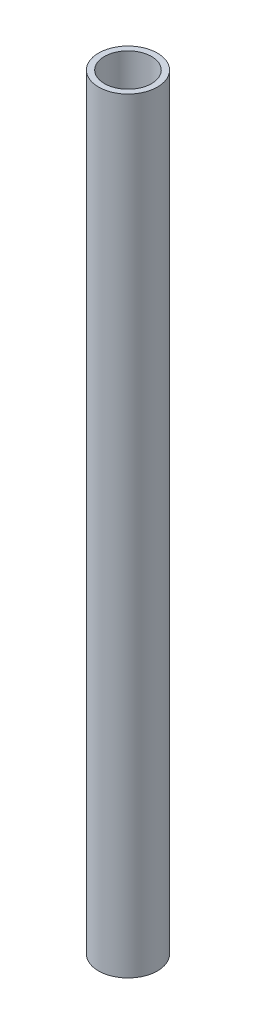
SolidWorks part; units mm, degrees
material "Hexcel AS4C (3000 丝)"
ref_plane "前视基准面" through (0, 0, 0) normal (0, 0, 1) x (1, 0, 0)
ref_plane "上视基准面" through (0, 0, 0) normal (0, 1, 0) x (1, 0, 0)
ref_plane "右视基准面" through (0, 0, 0) normal (1, 0, 0) x (0, 0, -1)
sketch "草图1" plane through (0, 0, 0) normal (0, 1, 0) x (1, 0, 0)
  circle A0 centre (0, 0) radius 10
  circle A1 centre (0, 0) radius 8
  dimension "D1" = 20
  dimension "D2" = 16
extrude "凸台-拉伸1" add sketch "草图1" along normal blind 260
